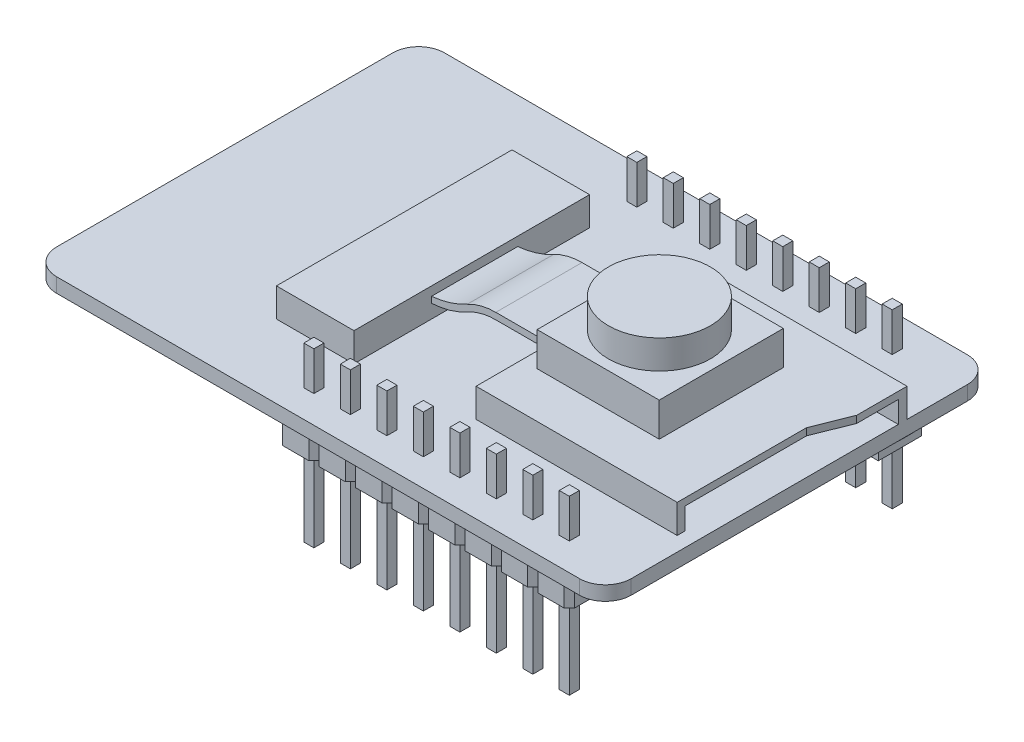
SolidWorks part; units mm, degrees
ref_plane "前视基准面" through (0, 0, 0) normal (0, 0, 1) x (1, 0, 0)
ref_plane "上视基准面" through (0, 0, 0) normal (0, 1, 0) x (1, 0, 0)
ref_plane "右视基准面" through (0, 0, 0) normal (1, 0, 0) x (0, 0, -1)
sketch "草图1" plane through (0, 0, 0) normal (0, 1, 0) x (1, 0, 0)
  line L0 (-20, 13.5) -> (20, 13.5)
  line L1 (-20, 13.5) -> (-20, -13.5)
  line L2 (20, 13.5) -> (20, -13.5)
  line L3 (-20, -13.5) -> (20, -13.5)
  line L4 (-20, 13.5) -> (20, -13.5) construction
  line L5 (20, 13.5) -> (-20, -13.5) construction
  point P1 (0, 0)
extrude "凸台-拉伸1" add sketch "草图1" along normal blind 1
fillet "圆角1" radius 1.8 4 edges at (-20, 0.5, 13.5) (-20, 0.5, -13.5) (20, 0.5, -13.5) (20, 0.5, 13.5)
sketch "草图4" plane through (0, 0, 0) normal (0, -1, 0) x (1, 0, 0)
  line L0 (-20, -11.7) -> (-20, 11.7) construction
  line L1 (-20, 9) -> (5.5, 9)
  line L2 (-20, 9) -> (-20, -9)
  line L3 (-20, -9) -> (5.5, -9)
  line L4 (5.5, 9) -> (5.5, -9)
  line L5 (-24.7231, 0) -> (25.6877, 0) construction
  dimension "D1" = 18
  dimension "D2" = 25.5
extrude "esp32底板" add sketch "草图4" along normal blind 1
sketch "草图5" plane through (0, -1, 0) normal (0, -1, 0) x (1, 0, 0)
  line L0 (-27.2904, 0) -> (11.6436, 0) construction
  line L1 (-12.65, 2.15) -> (-9.41, 2.15)
  line L2 (-12.65, 2.15) -> (-12.65, -7.85)
  line L3 (-12.65, -7.85) -> (-9.0798, -7.85)
  line L5 (-9.41, 7.85) -> (4.35, 7.85)
  line L6 (-9.41, 7.85) -> (-9.41, 2.15)
  line L7 (-9.0798, -7.85) -> (4.35, -7.85)
  line L8 (4.35, 7.85) -> (4.35, -7.85)
  line L9 (5.5, -9) -> (5.5, 9) construction
  dimension "D1" = 10
  dimension "D2" = 15.7
  dimension "D3" = 3.24
  dimension "D4" = 5.7
  dimension "D5" = 17
  dimension "D6" = 1.15
extrude "esp32外壳" add sketch "草图5" along normal blind 2.4
sketch "草图6" plane through (0, -1, 0) normal (0, -1, 0) x (1, 0, 0)
  line L0 (-20, 9) -> (-20, -9) construction
  line L1 (-14, 8) -> (-11.2, 8)
  line L2 (-14, 8) -> (-14, 5.6)
  line L3 (-14, 5.6) -> (-11.2, 5.6)
  line L4 (-11.2, 8) -> (-11.2, 5.6)
  line L5 (5.5, 9) -> (-20, 9) construction
  dimension "D1" = 6
  dimension "D2" = 1
  dimension "D3" = 2.4
  dimension "D4" = 2.8
extrude "天线座子地" add sketch "草图6" along normal blind 0.5
sketch "草图7" plane through (0, -1.5, 0) normal (0, -1, 0) x (1, 0, 0)
  circle A0 centre (-12.6345, 6.845) radius 0.101
extrude "天线座子针" add sketch "草图7" along normal blind 0.5
sketch "草图8" plane through (0, -1.5, 0) normal (0, -1, 0) x (1, 0, 0)
  circle A0 centre (-12.6345, 6.845) radius 1
  circle A1 centre (-12.6345, 6.845) radius 0.7746
  dimension "D1" = 2
extrude "天线座子" add sketch "草图8" along normal blind 0.5
sketch "草图9" plane through (0, -1, 0) normal (0, -1, 0) x (1, 0, 0)
  line L0 (-15.5448, -7.9938) -> (-18.5448, -7.9938)
  line L1 (-18.5448, -7.9938) -> (-18.5448, -4.9938)
  line L2 (-18.5448, -4.9938) -> (-15.5448, -4.9938)
  line L3 (-15.5448, -4.9938) -> (-15.5448, -1.9938)
  line L4 (-15.5448, -1.9938) -> (-18.5448, -1.9938)
  line L5 (-18.5448, -1.9938) -> (-18.5448, 1.0062)
  line L6 (-18.5448, 1.0062) -> (-15.5448, 1.0062)
  line L7 (-15.5448, 1.0062) -> (-15.5448, 4.0062)
  line L8 (-15.5448, 4.0062) -> (-18.5448, 4.0062)
  line L9 (-18.5448, 4.0062) -> (-18.5448, 7.0062)
  line L10 (-18.5448, 7.0062) -> (-15.5448, 7.0062)
  line L11 (-15.5448, 7.0062) -> (-15.5448, 8.3405)
  line L12 (-15.5448, 8.3405) -> (-19.2709, 8.3405)
  line L13 (-19.2709, 8.3405) -> (-19.2709, 3.4012)
  line L14 (-19.2709, 3.4012) -> (-16.0214, 3.4012)
  line L15 (-16.0214, 3.4012) -> (-16.0214, 1.5814)
  line L16 (-16.0214, 1.5814) -> (-19.2709, 1.5814)
  line L17 (-19.2709, 1.5814) -> (-19.2709, -2.7513)
  line L18 (-19.2709, -2.7513) -> (-16.0214, -2.7513)
  line L19 (-16.0214, -2.7513) -> (-16.0214, -4.3977)
  line L20 (-16.0214, -4.3977) -> (-19.2709, -4.3977)
  line L21 (-19.2709, -4.3977) -> (-19.2709, -8.6004)
  line L22 (-19.2709, -8.6004) -> (-13.8983, -8.6004)
  line L23 (-13.8983, -8.6004) -> (-13.8983, -7.9938)
  line L24 (-13.8983, -7.9938) -> (-15.5448, -7.9938)
extrude "天线" add sketch "草图9" along normal blind 0.1
sketch "草图10" plane through (0, 0, 0) normal (0, -1, 0) x (1, 0, 0)
  line L0 (20, 11.7) -> (20, -11.7) construction
  line L1 (12.5, 9.4) -> (16.5, 9.4)
  line L2 (12.5, 9.4) -> (12.5, 4.4)
  line L3 (12.5, 4.4) -> (16.5, 4.4)
  line L4 (16.5, 9.4) -> (16.5, 4.4)
  line L5 (-18.2, 13.5) -> (18.2, 13.5) construction
  dimension "D1" = 4
  dimension "D2" = 5
  dimension "D3" = 3.5
  dimension "D4" = 4.1
extrude "FLASH" add sketch "草图10" along normal blind 1.5
sketch "草图2" plane through (0, 0, 0) normal (0, -1, 0) x (1, 0, 0)
  line L0 (16.5, 19.3459) -> (16.5, -19.7584) construction
  line L5 (20, 11.7) -> (20, -11.7) construction
  line L6 (-3.8208, 12.1566) -> (-3.8208, 10.3237)
  line L7 (-3.8208, 10.3237) -> (-3.4672, 9.9701)
  line L8 (-3.4672, 9.9701) -> (-1.6343, 9.9701)
  line L9 (-1.6343, 9.9701) -> (-1.2808, 10.3237)
  line L11 (-1.2808, 12.1566) -> (-1.6343, 12.5101)
  line L20 (-1.6343, 12.5101) -> (-3.4672, 12.5101)
  line L21 (-3.4672, 12.5101) -> (-3.8208, 12.1566)
  line L24 (0.9057, 12.5101) -> (-0.9272, 12.5101)
  line L25 (1.2592, 12.1566) -> (0.9057, 12.5101)
  line L27 (0.9057, 9.9701) -> (1.2592, 10.3237)
  line L28 (-0.9272, 9.9701) -> (0.9057, 9.9701)
  line L29 (-1.2808, 10.3237) -> (-0.9272, 9.9701)
  line L31 (-0.9272, 12.5101) -> (-1.2808, 12.1566)
  line L32 (3.4457, 12.5101) -> (1.6128, 12.5101)
  line L33 (3.7992, 12.1566) -> (3.4457, 12.5101)
  line L35 (3.4457, 9.9701) -> (3.7992, 10.3237)
  line L36 (1.6128, 9.9701) -> (3.4457, 9.9701)
  line L37 (1.2592, 10.3237) -> (1.6128, 9.9701)
  line L39 (1.6128, 12.5101) -> (1.2592, 12.1566)
  line L40 (5.9857, 12.5101) -> (4.1528, 12.5101)
  line L41 (6.3392, 12.1566) -> (5.9857, 12.5101)
  line L43 (5.9857, 9.9701) -> (6.3392, 10.3237)
  line L44 (4.1528, 9.9701) -> (5.9857, 9.9701)
  line L45 (3.7992, 10.3237) -> (4.1528, 9.9701)
  line L47 (4.1528, 12.5101) -> (3.7992, 12.1566)
  line L48 (8.5257, 12.5101) -> (6.6928, 12.5101)
  line L49 (8.8792, 12.1566) -> (8.5257, 12.5101)
  line L51 (8.5257, 9.9701) -> (8.8792, 10.3237)
  line L52 (6.6928, 9.9701) -> (8.5257, 9.9701)
  line L53 (6.3392, 10.3237) -> (6.6928, 9.9701)
  line L55 (6.6928, 12.5101) -> (6.3392, 12.1566)
  line L56 (11.0657, 12.5101) -> (9.2328, 12.5101)
  line L57 (11.4192, 12.1566) -> (11.0657, 12.5101)
  line L59 (11.0657, 9.9701) -> (11.4192, 10.3237)
  line L60 (9.2328, 9.9701) -> (11.0657, 9.9701)
  line L61 (8.8792, 10.3237) -> (9.2328, 9.9701)
  line L63 (9.2328, 12.5101) -> (8.8792, 12.1566)
  line L64 (13.6057, 12.5101) -> (11.7728, 12.5101)
  line L65 (13.9592, 12.1566) -> (13.6057, 12.5101)
  line L67 (13.6057, 9.9701) -> (13.9592, 10.3237)
  line L68 (11.7728, 9.9701) -> (13.6057, 9.9701)
  line L69 (11.4192, 10.3237) -> (11.7728, 9.9701)
  line L71 (11.7728, 12.5101) -> (11.4192, 12.1566)
  line L72 (16.1457, 12.5101) -> (14.3128, 12.5101)
  line L73 (16.4992, 12.1566) -> (16.1457, 12.5101)
  line L74 (16.4992, 10.3237) -> (16.4992, 12.1566)
  line L75 (16.1457, 9.9701) -> (16.4992, 10.3237)
  line L76 (14.3128, 9.9701) -> (16.1457, 9.9701)
  line L77 (13.9592, 10.3237) -> (14.3128, 9.9701)
  line L79 (14.3128, 12.5101) -> (13.9592, 12.1566)
  line L80 (-30.9826, 0) -> (35.1621, 0) construction
  line L81 (14.3128, -12.5101) -> (13.9592, -12.1566)
  line L83 (13.9592, -10.3237) -> (14.3128, -9.9701)
  line L84 (14.3128, -9.9701) -> (16.1457, -9.9701)
  line L85 (16.1457, -9.9701) -> (16.4992, -10.3237)
  line L86 (16.4992, -10.3237) -> (16.4992, -12.1566)
  line L87 (16.4992, -12.1566) -> (16.1457, -12.5101)
  line L88 (16.1457, -12.5101) -> (14.3128, -12.5101)
  line L89 (11.7728, -12.5101) -> (11.4192, -12.1566)
  line L91 (11.4192, -10.3237) -> (11.7728, -9.9701)
  line L92 (11.7728, -9.9701) -> (13.6057, -9.9701)
  line L93 (13.6057, -9.9701) -> (13.9592, -10.3237)
  line L95 (13.9592, -12.1566) -> (13.6057, -12.5101)
  line L96 (13.6057, -12.5101) -> (11.7728, -12.5101)
  line L97 (9.2328, -12.5101) -> (8.8792, -12.1566)
  line L99 (8.8792, -10.3237) -> (9.2328, -9.9701)
  line L100 (9.2328, -9.9701) -> (11.0657, -9.9701)
  line L101 (11.0657, -9.9701) -> (11.4192, -10.3237)
  line L103 (11.4192, -12.1566) -> (11.0657, -12.5101)
  line L104 (11.0657, -12.5101) -> (9.2328, -12.5101)
  line L105 (6.6928, -12.5101) -> (6.3392, -12.1566)
  line L107 (6.3392, -10.3237) -> (6.6928, -9.9701)
  line L108 (6.6928, -9.9701) -> (8.5257, -9.9701)
  line L109 (8.5257, -9.9701) -> (8.8792, -10.3237)
  line L111 (8.8792, -12.1566) -> (8.5257, -12.5101)
  line L112 (8.5257, -12.5101) -> (6.6928, -12.5101)
  line L113 (4.1528, -12.5101) -> (3.7992, -12.1566)
  line L115 (3.7992, -10.3237) -> (4.1528, -9.9701)
  line L116 (4.1528, -9.9701) -> (5.9857, -9.9701)
  line L117 (5.9857, -9.9701) -> (6.3392, -10.3237)
  line L119 (6.3392, -12.1566) -> (5.9857, -12.5101)
  line L120 (5.9857, -12.5101) -> (4.1528, -12.5101)
  line L121 (1.6128, -12.5101) -> (1.2592, -12.1566)
  line L123 (1.2592, -10.3237) -> (1.6128, -9.9701)
  line L124 (1.6128, -9.9701) -> (3.4457, -9.9701)
  line L125 (3.4457, -9.9701) -> (3.7992, -10.3237)
  line L127 (3.7992, -12.1566) -> (3.4457, -12.5101)
  line L128 (3.4457, -12.5101) -> (1.6128, -12.5101)
  line L129 (-0.9272, -12.5101) -> (-1.2808, -12.1566)
  line L131 (-1.2808, -10.3237) -> (-0.9272, -9.9701)
  line L132 (-0.9272, -9.9701) -> (0.9057, -9.9701)
  line L133 (0.9057, -9.9701) -> (1.2592, -10.3237)
  line L135 (1.2592, -12.1566) -> (0.9057, -12.5101)
  line L136 (0.9057, -12.5101) -> (-0.9272, -12.5101)
  line L137 (-3.4672, -12.5101) -> (-3.8208, -12.1566)
  line L138 (-1.6343, -12.5101) -> (-3.4672, -12.5101)
  line L139 (-1.2808, -12.1566) -> (-1.6343, -12.5101)
  line L141 (-1.6343, -9.9701) -> (-1.2808, -10.3237)
  line L142 (-3.4672, -9.9701) -> (-1.6343, -9.9701)
  line L143 (-3.8208, -10.3237) -> (-3.4672, -9.9701)
  line L144 (-3.8208, -12.1566) -> (-3.8208, -10.3237)
  line L145 (-1.2808, 12.1566) -> (-1.2808, 10.3237) [skipped]
  line L146 (1.2592, 12.1566) -> (1.2592, 10.3237) [skipped]
  line L147 (3.7992, 12.1566) -> (3.7992, 10.3237) [skipped]
  line L148 (6.3392, 12.1566) -> (6.3392, 10.3237) [skipped]
  line L149 (8.8792, 12.1566) -> (8.8792, 10.3237) [skipped]
  line L150 (11.4192, 12.1566) -> (11.4192, 10.3237) [skipped]
  line L151 (13.9592, 12.1566) -> (13.9592, 10.3237) [skipped]
  dimension "D2" = 3.5
  dimension "D10" = 8
extrude "排针座" add sketch "草图2" along normal blind 2.3
sketch "草图3" plane through (0, -2.3, 0) normal (0, -1, 0) x (1, 0, 0)
  line L0 (-2.5508, 14.1529) -> (-2.5508, 9.1716) construction
  line L1 (-2.9008, 11.5901) -> (-2.2008, 11.5901)
  line L2 (-2.9008, 11.5901) -> (-2.9008, 10.8901)
  line L3 (-2.9008, 10.8901) -> (-2.2008, 10.8901)
  line L4 (-2.2008, 11.5901) -> (-2.2008, 10.8901)
  line L5 (-17.9073, 11.2401) -> (-15.9733, 11.2401) construction
  line L6 (-0.3608, 11.5901) -> (-0.3608, 10.8901)
  line L7 (-0.3608, 11.5901) -> (0.3392, 11.5901)
  line L8 (0.3392, 11.5901) -> (0.3392, 10.8901)
  line L9 (-0.3608, 10.8901) -> (0.3392, 10.8901)
  line L10 (2.1792, 11.5901) -> (2.1792, 10.8901)
  line L11 (2.1792, 11.5901) -> (2.8792, 11.5901)
  line L12 (2.8792, 11.5901) -> (2.8792, 10.8901)
  line L13 (2.1792, 10.8901) -> (2.8792, 10.8901)
  line L14 (4.7192, 11.5901) -> (4.7192, 10.8901)
  line L15 (4.7192, 11.5901) -> (5.4192, 11.5901)
  line L16 (5.4192, 11.5901) -> (5.4192, 10.8901)
  line L17 (4.7192, 10.8901) -> (5.4192, 10.8901)
  line L18 (7.2592, 11.5901) -> (7.2592, 10.8901)
  line L19 (7.2592, 11.5901) -> (7.9592, 11.5901)
  line L20 (7.9592, 11.5901) -> (7.9592, 10.8901)
  line L21 (7.2592, 10.8901) -> (7.9592, 10.8901)
  line L22 (9.7992, 11.5901) -> (9.7992, 10.8901)
  line L23 (9.7992, 11.5901) -> (10.4992, 11.5901)
  line L24 (10.4992, 11.5901) -> (10.4992, 10.8901)
  line L25 (9.7992, 10.8901) -> (10.4992, 10.8901)
  line L26 (12.3392, 11.5901) -> (12.3392, 10.8901)
  line L27 (12.3392, 11.5901) -> (13.0392, 11.5901)
  line L28 (13.0392, 11.5901) -> (13.0392, 10.8901)
  line L29 (12.3392, 10.8901) -> (13.0392, 10.8901)
  line L30 (14.8792, 11.5901) -> (14.8792, 10.8901)
  line L31 (14.8792, 11.5901) -> (15.5792, 11.5901)
  line L32 (15.5792, 11.5901) -> (15.5792, 10.8901)
  line L33 (14.8792, 10.8901) -> (15.5792, 10.8901)
  line L34 (-25.7488, 0) -> (27.3099, 0) construction
  line L35 (-2.9008, -10.8901) -> (-2.2008, -10.8901)
  line L36 (-2.9008, -11.5901) -> (-2.9008, -10.8901)
  line L37 (-2.9008, -11.5901) -> (-2.2008, -11.5901)
  line L38 (-2.2008, -11.5901) -> (-2.2008, -10.8901)
  line L39 (14.8792, -10.8901) -> (15.5792, -10.8901)
  line L40 (15.5792, -11.5901) -> (15.5792, -10.8901)
  line L41 (14.8792, -11.5901) -> (15.5792, -11.5901)
  line L42 (14.8792, -11.5901) -> (14.8792, -10.8901)
  line L43 (12.3392, -10.8901) -> (13.0392, -10.8901)
  line L44 (13.0392, -11.5901) -> (13.0392, -10.8901)
  line L45 (12.3392, -11.5901) -> (13.0392, -11.5901)
  line L46 (12.3392, -11.5901) -> (12.3392, -10.8901)
  line L47 (9.7992, -10.8901) -> (10.4992, -10.8901)
  line L48 (10.4992, -11.5901) -> (10.4992, -10.8901)
  line L49 (9.7992, -11.5901) -> (10.4992, -11.5901)
  line L50 (9.7992, -11.5901) -> (9.7992, -10.8901)
  line L51 (7.2592, -10.8901) -> (7.9592, -10.8901)
  line L52 (7.9592, -11.5901) -> (7.9592, -10.8901)
  line L53 (7.2592, -11.5901) -> (7.9592, -11.5901)
  line L54 (7.2592, -11.5901) -> (7.2592, -10.8901)
  line L55 (4.7192, -10.8901) -> (5.4192, -10.8901)
  line L56 (5.4192, -11.5901) -> (5.4192, -10.8901)
  line L57 (4.7192, -11.5901) -> (5.4192, -11.5901)
  line L58 (4.7192, -11.5901) -> (4.7192, -10.8901)
  line L59 (2.1792, -10.8901) -> (2.8792, -10.8901)
  line L60 (2.8792, -11.5901) -> (2.8792, -10.8901)
  line L61 (2.1792, -11.5901) -> (2.8792, -11.5901)
  line L62 (2.1792, -11.5901) -> (2.1792, -10.8901)
  line L63 (-0.3608, -10.8901) -> (0.3392, -10.8901)
  line L64 (0.3392, -11.5901) -> (0.3392, -10.8901)
  line L65 (-0.3608, -11.5901) -> (0.3392, -11.5901)
  line L66 (-0.3608, -11.5901) -> (-0.3608, -10.8901)
  dimension "D1" = 0.7
  dimension "D2" = 8
extrude "排针" add sketch "草图3" along normal mid plane 12
sketch "草图11" plane through (0, 0, 0) normal (0, -1, 0) x (1, 0, 0)
  line L0 (20, 11.7) -> (20, -11.7) construction
  line L1 (13.5, 2) -> (17, 2)
  line L2 (13.5, 2) -> (13.5, -4.5)
  line L3 (13.5, -4.5) -> (17, -4.5)
  line L4 (17, 2) -> (17, -4.5)
  line L6 (12.5, 4.4) -> (16.5, 4.4) construction
  dimension "D1" = 3.5
  dimension "D2" = 6.5
  dimension "D3" = 3
  dimension "D4" = 2.4
extrude "AMS1117" add sketch "草图11" along normal blind 1.5
sketch "草图12" plane through (0, 0, 0) normal (0, -1, 0) x (1, 0, 0)
  line L0 (20, 11.7) -> (20, -11.7) construction
  line L1 (15, -6.5) -> (19, -6.5)
  line L2 (15, -6.5) -> (15, -9.5)
  line L3 (15, -9.5) -> (19, -9.5)
  line L4 (19, -6.5) -> (19, -9.5)
  line L5 (18.2, -13.5) -> (-18.2, -13.5) construction
  dimension "D1" = 4
  dimension "D2" = 3
  dimension "D3" = 1
  dimension "D4" = 4
extrude "按键" add sketch "草图12" along normal blind 1.5
sketch "草图13" plane through (0, -1.5, 0) normal (0, -1, 0) x (1, 0, 0)
  line L0 (19, -9.5) -> (19, -6.5) construction
  line L1 (15, -9.5) -> (19, -9.5) construction
  circle A0 centre (17, -8) radius 0.8706
  dimension "D1" = 2
  dimension "D2" = 1.5
extrude "按键按键" add sketch "草图13" along normal blind 0.5
sketch "草图14" plane through (0, 0, 0) normal (0, -1, 0) x (1, 0, 0)
  line L0 (17, -4.5) -> (17, 2) construction
  line L1 (17, 0.5049) -> (18.7364, 0.5049)
  line L2 (17, 0.5049) -> (17, -2.8731)
  line L3 (17, -2.8731) -> (18.7364, -2.8731)
  line L4 (18.7364, 0.5049) -> (18.7364, -2.8731)
  line L5 (13.5, 2) -> (13.5, -4.5) construction
  line L6 (13.5, 1.4088) -> (11.4048, 1.4088)
  line L7 (13.5, 1.4088) -> (13.5, 0.4088)
  line L8 (13.5, 0.4088) -> (11.4048, 0.4088)
  line L9 (11.4048, 1.4088) -> (11.4048, 0.4088)
  line L10 (11.4048, 3.1692) -> (11.4048, -4.8238) construction
  line L11 (13.5038, -0.6603) -> (11.4086, -0.6603)
  line L12 (13.5038, -0.6603) -> (13.5038, -1.6603)
  line L13 (13.5038, -1.6603) -> (11.4086, -1.6603)
  line L14 (11.4086, -0.6603) -> (11.4086, -1.6603)
  line L15 (13.5038, -2.7538) -> (11.4086, -2.7538)
  line L16 (13.5038, -2.7538) -> (13.5038, -3.7538)
  line L17 (13.5038, -3.7538) -> (11.4086, -3.7538)
  line L18 (11.4086, -2.7538) -> (11.4086, -3.7538)
  line L19 (14.5, 8.9826) -> (14.5, 5.1892) construction
  line L20 (18.2667, 9.8153) -> (18.2667, 3.385) construction
  line L21 (16.5, 4.4) -> (16.5, 9.4) construction
  line L22 (16.5, 9.0521) -> (18.2667, 9.0521)
  line L23 (16.5, 9.0521) -> (16.5, 8.4738)
  line L24 (16.5, 8.4738) -> (18.2667, 8.4738)
  line L25 (18.2667, 9.0521) -> (18.2667, 8.4738)
  line L26 (16.5, 4.4) -> (16.5, 9.4) construction
  line L27 (16.5, 7.922) -> (18.2667, 7.922)
  line L28 (16.5, 7.922) -> (16.5, 7.3437)
  line L29 (16.5, 7.3437) -> (18.2667, 7.3437)
  line L30 (18.2667, 7.922) -> (18.2667, 7.3437)
  line L31 (16.5, 6.6234) -> (18.2667, 6.6234)
  line L32 (16.5, 6.6234) -> (16.5, 6.0451)
  line L33 (16.5, 6.0451) -> (18.2667, 6.0451)
  line L34 (18.2667, 6.6234) -> (18.2667, 6.0451)
  line L35 (16.5, 5.3875) -> (18.2667, 5.3875)
  line L36 (16.5, 5.3875) -> (16.5, 4.8093)
  line L37 (16.5, 4.8093) -> (18.2667, 4.8093)
  line L38 (18.2667, 5.3875) -> (18.2667, 4.8093)
  line L39 (12.5, 9.4) -> (12.5, 4.4) construction
  line L40 (12.5, 4.8093) -> (10.7333, 4.8093)
  line L41 (10.7333, 5.3875) -> (10.7333, 4.8093)
  line L42 (12.5, 5.3875) -> (10.7333, 5.3875)
  line L43 (12.5, 5.3875) -> (12.5, 4.8093)
  line L44 (12.5, 6.0451) -> (10.7333, 6.0451)
  line L45 (10.7333, 6.6234) -> (10.7333, 6.0451)
  line L46 (12.5, 6.6234) -> (10.7333, 6.6234)
  line L47 (12.5, 6.6234) -> (12.5, 6.0451)
  line L48 (12.5, 7.3437) -> (10.7333, 7.3437)
  line L49 (10.7333, 7.922) -> (10.7333, 7.3437)
  line L50 (12.5, 7.922) -> (10.7333, 7.922)
  line L51 (12.5, 7.922) -> (12.5, 7.3437)
  line L52 (12.5, 8.4738) -> (10.7333, 8.4738)
  line L53 (10.7333, 9.0521) -> (10.7333, 8.4738)
  line L54 (12.5, 9.0521) -> (10.7333, 9.0521)
  line L55 (12.5, 9.0521) -> (12.5, 8.4738)
  line L56 (15, -6.5) -> (15, -9.5) construction
  line L57 (15, -7.4368) -> (14.5, -7.4368)
  line L58 (15, -7.4368) -> (15, -8.4368)
  line L59 (15, -8.4368) -> (14.5, -8.4368)
  line L60 (14.5, -7.4368) -> (14.5, -8.4368)
  line L61 (19, -9.5) -> (19, -6.5) construction
  line L62 (19, -7.4368) -> (19.5118, -7.4368)
  line L63 (19, -7.4368) -> (19, -8.4368)
  line L64 (19, -8.4368) -> (19.5118, -8.4368)
  line L65 (19.5118, -7.4368) -> (19.5118, -8.4368)
extrude "引脚" add sketch "草图14" along normal blind 0.5
sketch "草图15" plane through (0, 1, 0) normal (0, 1, 0) x (1, 0, 0)
  line L1 (5, 7.5) -> (5, -7.5)
  line L2 (5, -7.5) -> (19, -7.5)
  line L3 (19, -7.5) -> (19, 1.5)
  line L4 (19, 1.5) -> (20, 4)
  line L5 (20, 4) -> (20, 7.5)
  line L6 (20, 7.5) -> (5, 7.5)
  line L7 (20, -11.7) -> (20, 11.7) construction
  line L8 (18.2, 13.5) -> (-18.2, 13.5) construction
  dimension "D1" = 15
  dimension "D2" = 15
  dimension "D3" = 14
  dimension "D4" = 9
  dimension "D5" = 3.5
  dimension "D6" = 6
extrude "SD卡" add sketch "草图15" along normal blind 2
sketch "草图16" plane through (20, 0, 0) normal (1, 0, 0) x (0, 0, -1)
  line L0 (-7.5, 1) -> (1.5, 1) construction
  line L1 (6.8932, 2.5068) -> (-6.9498, 2.5068)
  line L2 (6.8932, 2.5068) -> (6.8932, 1)
  line L3 (6.8932, 1) -> (-6.9498, 1)
  line L4 (-6.9498, 2.5068) -> (-6.9498, 1)
extrude "SD卡掏空" cut sketch "草图16" against normal blind 14
sketch "草图17" plane through (0, 3, 0) normal (0, 1, 0) x (1, 0, 0)
  line L0 (-10.8413, 0) -> (2.6212, 0) construction
  line L1 (6.0703, 4.32) -> (14.5703, 4.32)
  line L2 (6.0703, 4.32) -> (6.0703, -4.32)
  line L3 (6.0703, -4.32) -> (14.5703, -4.32)
  line L4 (14.5703, 4.32) -> (14.5703, -4.32)
  dimension "D1" = 8.5
  dimension "D2" = 8.64
extrude "OV2640" add sketch "草图17" along normal blind 2.36
sketch "草图18" plane through (0, 5.36, 0) normal (0, 1, 0) x (1, 0, 0)
  line L2 (14.5703, -4.32) -> (14.5703, 4.32) construction
  circle A0 centre (10.3203, -0.0597) radius 3.55
  dimension "D1" = 7.1
  dimension "D2" = 4.25
extrude "OV2640镜头" add sketch "草图18" along normal blind 2
sketch "草图19" plane through (0, 1, 0) normal (0, 1, 0) x (1, 0, 0)
  line L0 (18.2, 13.5) -> (-18.2, 13.5) construction
  line L1 (-8, 8) -> (-2.6, 8)
  line L2 (-8, 8) -> (-8, -8.4)
  line L3 (-8, -8.4) -> (-2.6, -8.4)
  line L4 (-2.6, 8) -> (-2.6, -8.4)
  line L5 (-20, 11.7) -> (-20, -11.7) construction
  dimension "D1" = 16.4
  dimension "D2" = 5.4
  dimension "D3" = 5.5
  dimension "D4" = 12
extrude "凸台-拉伸18" add sketch "草图19" along normal blind 2
sketch "草图20" plane through (0, 0, 0) normal (0, 0, 1) x (1, 0, 0)
  line L0 (6.0703, 3.6432) -> (1.8743, 3.6432)
  line L1 (6.0703, 5.36) -> (6.0703, 3) construction
  line L2 (-2.9008, 1) -> (-2.9008, 3.7) construction
  line L3 (-2.9008, 2.35) -> (-2.9008, 1.9429)
  line L4 (1.8743, 3.1881) -> (6.0703, 3.1881)
  line L5 (6.0703, 3.1881) -> (6.0703, 3.6432)
  arc A0 (1.8743, 3.6432) -> (-0.1139, 3.1359) centre (1.8743, -0.5062) ccw
  arc A1 (-0.1139, 3.1359) -> (-2.9008, 2.35) centre (-3.2254, 8.8358) cw
  arc A2 (-2.9008, 1.9429) -> (-0.1139, 2.6697) centre (-2.9008, 7.65) ccw
  arc A3 (-0.1139, 2.6697) -> (1.8743, 3.1881) centre (1.8743, -0.8834) cw
extrude "凸台-拉伸19" add sketch "草图20" along normal mid plane 6
